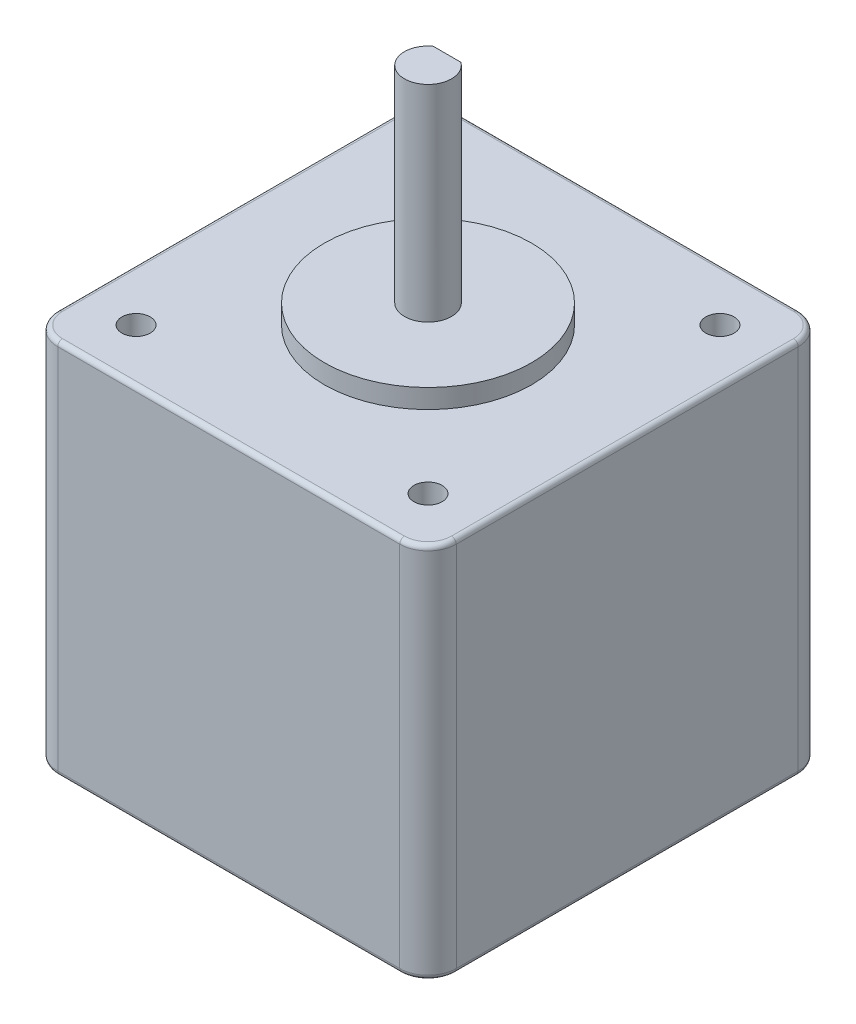
SolidWorks part; units mm, degrees
ref_plane "Front Plane" through (0, 0, 0) normal (0, 0, 1) x (1, 0, 0)
ref_plane "Top Plane" through (0, 0, 0) normal (0, 1, 0) x (1, 0, 0)
ref_plane "Right Plane" through (0, 0, 0) normal (1, 0, 0) x (0, 0, -1)
sketch "Sketch2" plane through (0, 0, 0) normal (0, 1, 0) x (1, 0, 0)
  line L0 (0, 42.3) -> (5.655, 36.645) construction
  line L1 (0, 0) -> (42.3, 0)
  line L2 (0, 0) -> (0, 42.3)
  line L3 (0, 42.3) -> (42.3, 42.3)
  line L4 (42.3, 0) -> (42.3, 42.3)
  line L5 (5.655, 36.645) -> (36.645, 36.645) construction
  line L6 (5.655, 36.645) -> (5.655, 5.655) construction
  line L7 (5.655, 5.655) -> (36.645, 5.655) construction
  line L8 (36.645, 36.645) -> (36.645, 5.655) construction
  line L9 (36.645, 5.655) -> (42.3, 0) construction
  line L10 (36.645, 36.645) -> (42.3, 42.3) construction
  line L11 (0, 0) -> (5.655, 5.655) construction
  circle A0 centre (5.655, 36.645) radius 1.5
  circle A1 centre (36.645, 36.645) radius 1.5
  circle A2 centre (36.645, 5.655) radius 1.5
  circle A3 centre (5.655, 5.655) radius 1.5
  dimension "D3" = 3
  dimension "D1" = 42.3
  dimension "D2" = 30.99
extrude "Boss-Extrude1" add sketch "Sketch2" along normal blind 40
sketch "Sketch3" plane through (0, 40, 0) normal (0, 1, 0) x (1, 0, 0)
  line L0 (0, 42.3) -> (42.3, 0) construction
  circle A0 centre (21.15, 21.15) radius 11
  point P6 (21.15, 21.15)
  dimension "D1" = 22
extrude "Boss-Extrude2" add sketch "Sketch3" along normal blind 2.03
sketch "Sketch4" plane through (0, 42.03, 0) normal (0, 1, 0) x (1, 0, 0)
  circle A0 centre (21.15, 21.15) radius 2.5
  circle A1 centre (21.15, 21.15) radius 11 construction
  dimension "D1" = 5
extrude "Boss-Extrude3" add sketch "Sketch4" along normal blind 21.85
sketch "Sketch5" plane through (0, 63.88, 0) normal (0, 1, 0) x (1, 0, 0)
  line L0 (19.677, 23.17) -> (22.623, 23.17)
  circle A0 centre (21.15, 21.15) radius 2.5 construction
  arc A1 (19.677, 23.17) -> (22.623, 23.17) centre (21.15, 21.15) cw
  dimension "D1" = 4.52
extrude "Cut-Extrude1" cut sketch "Sketch5" against normal blind 14.86
fillet "Fillet1" radius 3 4 edges at (0, 20, -42.3) (42.3, 20, -42.3) (42.3, 20, 0) (0, 20, 0)
fillet "Fillet2" radius 0.5 16 edges at (0.8787, 0, -0.8787) (0, 0, -21.15) (0.8787, 0, -41.4213) (21.15, 0, -42.3) (41.4213, 0, -41.4213) (42.3, 0, -21.15) (41.4213, 0, -0.8787) (0.8787, 40, -0.8787) (0, 40, -21.15) (0.8787, 40, -41.4213) (21.15, 40, -42.3) (41.4213, 40, -41.4213) (42.3, 40, -21.15) (41.4213, 40, -0.8787) (21.15, 0, 0) (21.15, 40, 0)
